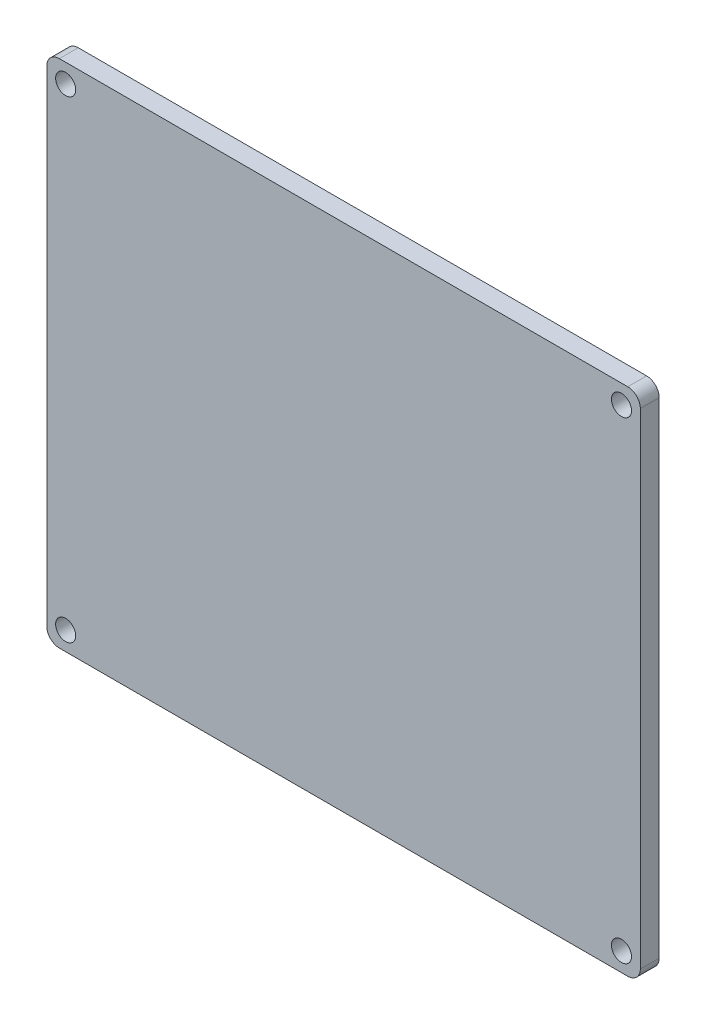
SolidWorks part; units mm, degrees
ref_plane "前视基准面" through (0, 0, 0) normal (0, 0, 1) x (1, 0, 0)
ref_plane "上视基准面" through (0, 0, 0) normal (0, 1, 0) x (1, 0, 0)
ref_plane "右视基准面" through (0, 0, 0) normal (1, 0, 0) x (0, 0, -1)
other "Configuration Table"
sketch "草图1" plane through (0, 0, 0) normal (0, 0, 1) x (1, 0, 0)
  line L0 (44.2, 37.6) -> (44.2, -37.6) construction
  line L1 (40.2, 33.6) -> (-40.2, 33.6)
  line L2 (40.2, 33.6) -> (40.2, -33.6)
  line L3 (40.2, -33.6) -> (-40.2, -33.6)
  line L4 (-40.2, 33.6) -> (-40.2, -33.6)
  line L5 (44.2, -37.6) -> (-44.2, -37.6) construction
  line L6 (-44.2, 37.6) -> (-44.2, -37.6) construction
  line L7 (44.2, 37.6) -> (-44.2, 37.6) construction
  line L8 (47.2, 40.6) -> (47.2, -40.6)
  line L9 (47.2, -40.6) -> (-47.2, -40.6)
  line L10 (-47.2, 40.6) -> (-47.2, -40.6)
  line L11 (47.2, 40.6) -> (-47.2, 40.6)
  circle A1 centre (40.2, -33.6) radius 1.5
  circle A2 centre (40.2, -33.6) radius 1.5
  circle A3 centre (-40.2, -33.6) radius 1.5
  circle A4 centre (-40.2, -33.6) radius 1.5
  circle A5 centre (-40.2, 33.6) radius 1.5
  circle A6 centre (-40.2, 33.6) radius 1.5
  circle A7 centre (40.2, 33.6) radius 1.5
  circle A8 centre (40.2, 33.6) radius 1.5
  circle A9 centre (44.2, 37.6) radius 1.6
  circle A10 centre (44.2, -37.6) radius 1.6
  circle A11 centre (-44.2, 37.6) radius 1.6
  circle A12 centre (-44.2, -37.6) radius 1.6
  dimension "D6" = 3.2
  dimension "D7" = 7
  dimension "D1" = 0
  dimension "D2" = 0
  dimension "D3" = 0
  dimension "D4" = 0
  dimension "D5" = 4
extrude "凸台-拉伸1" add sketch "草图1" along normal blind 3 contours L8 L11 L10 L9 A12 A11 A10 A9 A8 L2 A2 L3 A4 L4 A6 L1 | A8 L1 A6 L4 A4 L3 A2 L2 | L1 A6 L4 | L2 A8 L1 | L1 A8 L2 | L4 A6 L1 | L4 A4 L3 | L3 A4 L4 | L2 A2 L3 | L3 A2 L2
fillet "圆角1" radius 2 4 edges at (47.2, -40.6, 1.5) (-47.2, -40.6, 1.5) (-47.2, 40.6, 1.5) (47.2, 40.6, 1.5)
